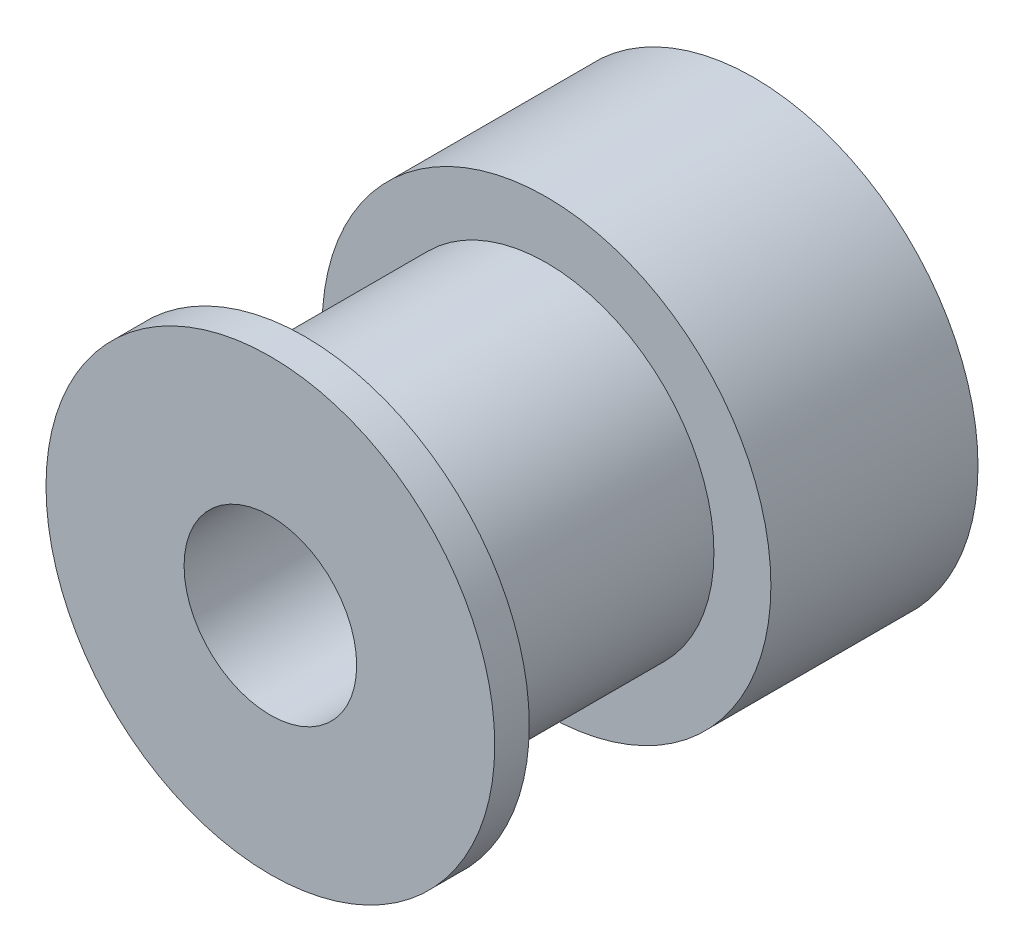
SolidWorks part; units mm, degrees
ref_plane "前视基准面" through (0, 0, 0) normal (0, 0, 1) x (1, 0, 0)
ref_plane "上视基准面" through (0, 0, 0) normal (0, 1, 0) x (1, 0, 0)
ref_plane "右视基准面" through (0, 0, 0) normal (1, 0, 0) x (0, 0, -1)
sketch "草图1" plane through (0, 0, 0) normal (0, 0, 1) x (1, 0, 0)
  circle A0 centre (0, 0) radius 2.5
  circle A1 centre (0, 0) radius 6.5
  dimension "D1" = 5
  dimension "D2" = 13
extrude "凸台-拉伸1" add sketch "草图1" along normal blind 6
sketch "草图2" plane through (0, 0, 6) normal (0, 0, 1) x (1, 0, 0)
  circle A0 centre (0, 0) radius 2.5
  circle A1 centre (0, 0) radius 4.85
  dimension "D1" = 9.7
extrude "凸台-拉伸2" add sketch "草图2" along normal blind 7
sketch "草图3" plane through (0, 0, 13) normal (0, 0, 1) x (1, 0, 0)
  circle A0 centre (0, 0) radius 2.5
  circle A1 centre (0, 0) radius 6.5
extrude "凸台-拉伸3" add sketch "草图3" along normal blind 1
